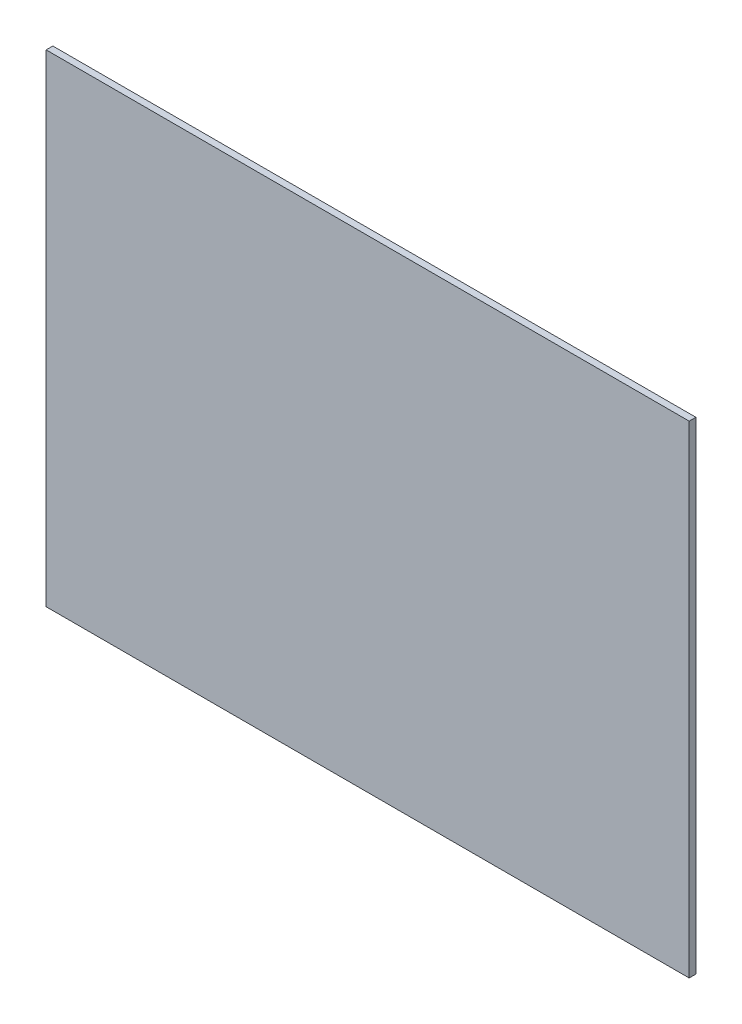
SolidWorks part; units mm, degrees
material "Custom Plastic"
ref_plane "X-Y Datum" through (0, 0, 0) normal (0, 0, 1) x (1, 0, 0)
ref_plane "X-Z Datum" through (0, 0, 0) normal (0, 1, 0) x (1, 0, 0)
ref_plane "Y-Z Datum" through (0, 0, 0) normal (1, 0, 0) x (0, 0, -1)
sketch "Sketch2" plane through (0, 0, 0) normal (0, 0, 1) x (1, 0, 0)
  line L1 (-304.8, 228.6) -> (304.8, 228.6)
  line L2 (-304.8, 228.6) -> (-304.8, -228.6)
  line L3 (-304.8, -228.6) -> (304.8, -228.6)
  line L4 (304.8, 228.6) -> (304.8, -228.6)
  line L5 (-304.8, 228.6) -> (304.8, -228.6) construction
  line L6 (-304.8, -228.6) -> (304.8, 228.6) construction
  point P0 (0, 0)
  dimension "D1" = 609.6
  dimension "D2" = 457.2
extrude "Boss-Extrude1" add sketch "Sketch2" along normal blind 6.35
